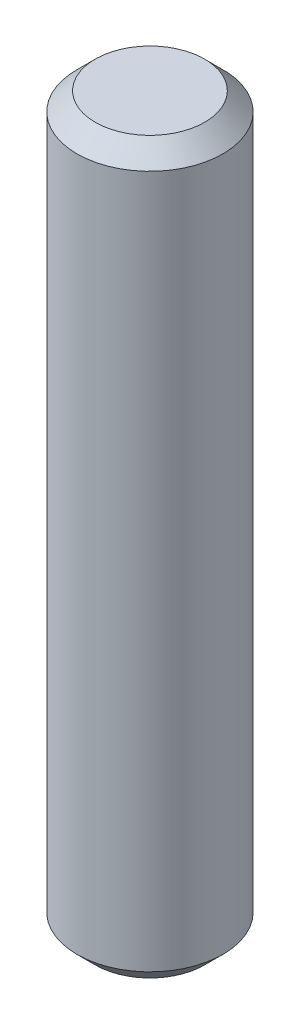
SolidWorks part; units mm, degrees
ref_plane "Front Plane" through (0, 0, 0) normal (0, 0, 1) x (1, 0, 0)
ref_plane "Top Plane" through (0, 0, 0) normal (0, 1, 0) x (1, 0, 0)
ref_plane "Right Plane" through (0, 0, 0) normal (1, 0, 0) x (0, 0, -1)
sketch "Sketch1" plane through (0, 0, 0) normal (0, 1, 0) x (1, 0, 0)
  circle A0 centre (0, 0) radius 2
  dimension "D1" = 4
extrude "Boss-Extrude1" add sketch "Sketch1" along normal blind 20
chamfer "Chamfer1" distance 0.5 angle 45 1 edges at (0, 20, 2)
chamfer "Chamfer2" distance 0.5 angle 45 1 edges at (0, 0, 2)
